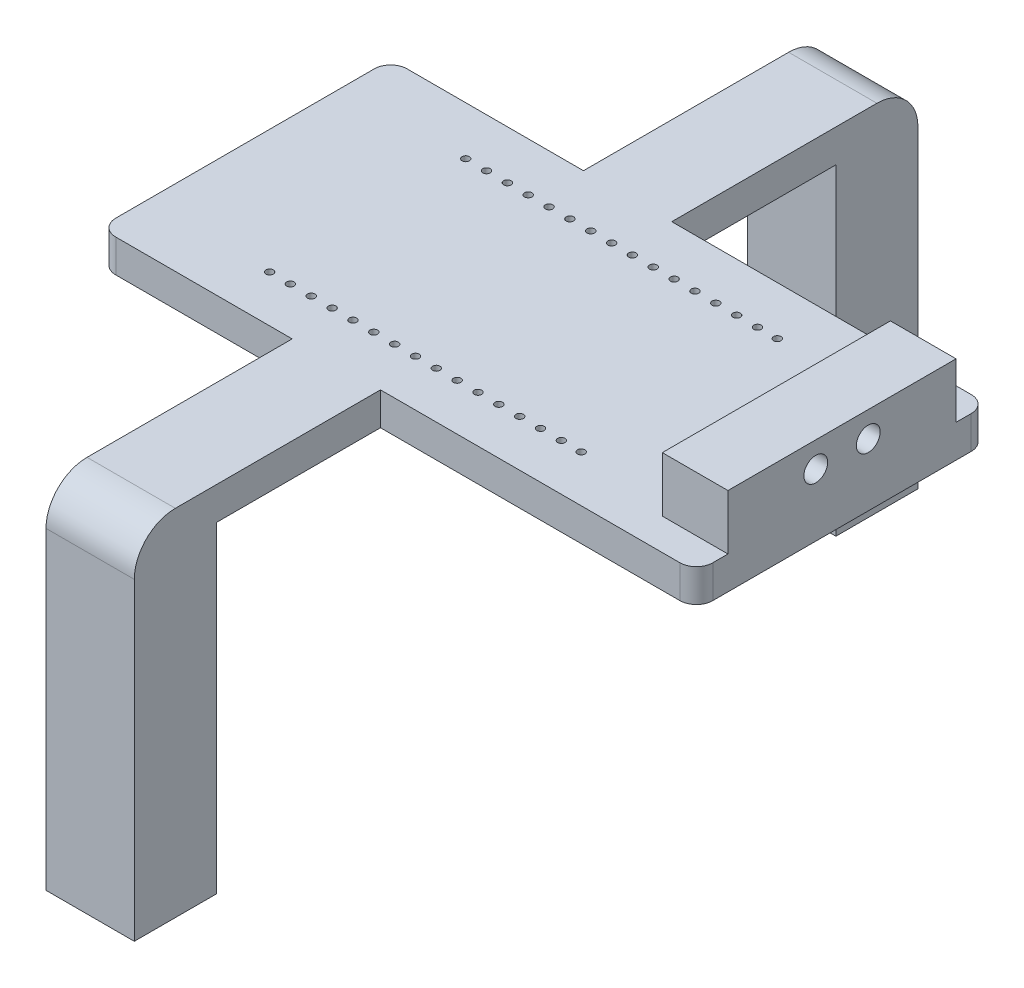
SolidWorks part; units mm, degrees
ref_plane "Front Plane" through (0, 0, 0) normal (0, 0, 1) x (1, 0, 0)
ref_plane "Top Plane" through (0, 0, 0) normal (0, 1, 0) x (1, 0, 0)
ref_plane "Right Plane" through (0, 0, 0) normal (1, 0, 0) x (0, 0, -1)
sketch "Sketch1" plane through (0, 0, 0) normal (0, 1, 0) x (1, 0, 0)
  line L7 (-5.5453, -3.1231) -> (67.2047, -3.1231)
  line L8 (-5.5453, -3.1231) -> (-5.5453, 32.3769)
  line L9 (-5.5453, 32.3769) -> (67.2047, 32.3769)
  line L10 (67.2047, -3.1231) -> (67.2047, 32.3769)
  point P0 (0, 0)
  point P18 (0, 0)
  dimension "D1" = 72.75
  dimension "D2" = 35.5
extrude "Boss-Extrude1" add sketch "Sketch1" along normal blind 2
sketch "Sketch7" plane through (0, 2, 0) normal (0, 1, 0) x (1, 0, 0)
  line L2 (17.9499, 32.3769) -> (17.9499, 62.3769)
  line L3 (17.9499, 62.3769) -> (28.7094, 62.3769)
  line L4 (28.7094, 32.3769) -> (28.7094, 62.3769)
  line L5 (23.3297, 44.5136) -> (28.7094, 62.3769) construction
  line L6 (17.9499, 62.3769) -> (23.3297, 44.5136) construction
  line L7 (17.9499, 32.3769) -> (28.7094, 32.3769)
  line L8 (67.2047, 32.3769) -> (-5.5453, 32.3769) construction
  point P0 (23.3297, 24.3769)
  point P2 (0, 0)
  dimension "D1" = 30
extrude "Boss-Extrude4" add sketch "Sketch7" against normal blind 4
sketch "Sketch8" plane through (0, 2, 0) normal (0, 1, 0) x (1, 0, 0)
  line L0 (-5.5453, 14.6269) -> (67.2047, 14.6269)
  line L1 (-5.5453, 32.3769) -> (-5.5453, -3.1231) construction
  line L2 (67.2047, -3.1231) -> (67.2047, 32.3769) construction
ref_plane "Plane2" through (0, 0, -14.6269) normal (0, 0, 1) x (1, 0, 0)
mirror "Mirror3" about plane through (0, 0, -14.6269) normal (0, 0, 1) of "Boss-Extrude4"
sketch "Sketch10" plane through (0, 2, 0) normal (0, 1, 0) x (1, 0, 0)
  line L0 (17.9499, 62.3769) -> (17.9499, 52.3769)
  line L1 (17.9499, 62.3769) -> (17.9499, 32.3769) construction
  line L2 (17.9499, 52.3769) -> (28.7094, 52.3769)
  line L3 (28.7094, 32.3769) -> (28.7094, 62.3769) construction
  line L4 (28.7094, 52.3769) -> (28.7094, 62.3769)
  line L5 (28.7094, 62.3769) -> (17.9499, 62.3769)
  dimension "D1" = 10
extrude "Boss-Extrude5" add sketch "Sketch10" against normal blind 43.2
mirror "Mirror4" about plane through (0, 0, -14.6269) normal (0, 0, 1) of "Boss-Extrude5"
fillet "Fillet2" radius 5 2 edges at (23.3297, 2, -62.3769) (23.3297, 2, 33.1231)
sketch "Sketch12" plane through (0, 0, 0) normal (0, -1, 0) x (1, 0, 0)
  line L0 (-5.5453, 3.1231) -> (67.2047, 3.1231)
  line L1 (-5.5453, 3.1231) -> (-5.5453, -32.3769)
  line L2 (67.2047, 3.1231) -> (67.2047, -32.3769)
  line L3 (-5.5453, -32.3769) -> (67.2047, -32.3769)
  line L4 (17.9499, -32.3769) -> (-5.5453, -32.3769) construction
  point P0 (0, 0)
extrude "Boss-Extrude6" add sketch "Sketch12" along normal blind 2
fillet "Fillet4" radius 2 4 edges at (67.2047, 0, 3.1231) (-5.5453, 0, 3.1231) (-5.5453, 0, -32.3769) (67.2047, 0, -32.3769)
ref_plane "Plane3" through (67.2047, 0, 0) normal (1, 0, 0) x (0, 0, -1)
sketch "Sketch16" plane through (67.2047, 0, 0) normal (1, 0, 0) x (0, 0, -1)
  line L1 (0.7269, 2) -> (28.5269, 2)
  line L3 (28.5269, 8.7) -> (28.5269, 2)
  line L5 (0.7269, 8.7) -> (28.5269, 8.7)
  line L7 (0.7269, 8.7) -> (0.7269, 2)
  line L9 (-1.1231, 2) -> (30.3769, 2) construction
  line L10 (-3.1231, -2) -> (-3.1231, 2) construction
  line L11 (32.3769, -2) -> (32.3769, 2) construction
  point P1 (14.6269, 2)
  dimension "D1" = 27.8
  dimension "D2" = 6.7
  dimension "D3" = 3.85
  dimension "D4" = 3.85
extrude "Boss-Extrude8" add sketch "Sketch16" against normal blind 8 contours L5 L3 L1 L7
sketch "Sketch19" plane through (67.2047, 0, 0) normal (1, 0, 0) x (0, 0, -1)
  line L0 (11.4269, 5.6119) -> (17.8269, 5.6119)
  line L1 (14.6269, 40.0125) -> (14.6269, -40.0125) construction
  circle A0 centre (17.8269, 5.6119) radius 1.45
  circle A1 centre (11.4269, 5.6119) radius 1.45
  point P4 (14.6269, 5.6119)
  dimension "D1" = 2.9
extrude "Cut-Extrude2" cut sketch "Sketch19" against normal blind 4
sketch "Sketch20" plane through (0, 2, 0) normal (0, 1, 0) x (1, 0, 0)
  line L0 (1.7408, 25.2114) -> (59.4908, 25.2114) construction
  line L1 (1.7408, 27.7114) -> (59.4908, 27.7114) construction
  line L2 (8.2408, 27.7114) -> (8.2408, 25.2114) construction
  line L3 (48.7558, 27.7114) -> (48.7558, 25.2114) construction
  line L4 (9.0608, 26.4614) -> (47.9358, 26.4614) construction
  line L5 (10.7808, 27.7114) -> (10.7808, 26.4614) construction
  line L6 (10.7808, 26.4614) -> (10.7808, 25.2114) construction
  line L7 (10.7808, 27.0864) -> (8.2408, 27.0864) construction
  line L8 (9.5108, 27.0864) -> (9.5108, 26.4614) construction
  line L9 (8.2408, 26.4614) -> (9.0608, 26.4614) construction
  line L10 (47.9358, 26.4614) -> (48.7558, 26.4614) construction
  line L11 (30.6158, 25.2114) -> (30.6158, 14.5114) construction
  line L12 (30.6158, 14.5114) -> (32.5949, 14.5114)
  line L13 (47.9358, 2.5614) -> (48.7558, 2.5614) construction
  line L14 (8.2408, 2.5614) -> (9.0608, 2.5614) construction
  line L15 (9.5108, 1.9364) -> (9.5108, 2.5614) construction
  line L16 (10.7808, 1.9364) -> (8.2408, 1.9364) construction
  line L17 (10.7808, 2.5614) -> (10.7808, 3.8114) construction
  line L18 (10.7808, 1.3114) -> (10.7808, 2.5614) construction
  line L19 (9.0608, 2.5614) -> (47.9358, 2.5614) construction
  line L20 (48.7558, 1.3114) -> (48.7558, 3.8114) construction
  line L21 (8.2408, 1.3114) -> (8.2408, 3.8114) construction
  circle A0 centre (9.5108, 26.4614) radius 0.45
  circle A1 centre (12.0508, 26.4614) radius 0.45
  circle A2 centre (14.5908, 26.4614) radius 0.45
  circle A3 centre (17.1308, 26.4614) radius 0.45
  circle A4 centre (19.6708, 26.4614) radius 0.45
  circle A5 centre (22.2108, 26.4614) radius 0.45
  circle A6 centre (24.7508, 26.4614) radius 0.45
  circle A7 centre (27.2908, 26.4614) radius 0.45
  circle A8 centre (29.8308, 26.4614) radius 0.45
  circle A9 centre (32.3708, 26.4614) radius 0.45
  circle A10 centre (34.9108, 26.4614) radius 0.45
  circle A11 centre (37.4508, 26.4614) radius 0.45
  circle A12 centre (39.9908, 26.4614) radius 0.45
  circle A13 centre (42.5308, 26.4614) radius 0.45
  circle A14 centre (45.0708, 26.4614) radius 0.45
  circle A15 centre (47.4858, 26.4614) radius 0.45
  circle A16 centre (47.4858, 2.5614) radius 0.45
  circle A17 centre (45.0708, 2.5614) radius 0.45
  circle A18 centre (42.5308, 2.5614) radius 0.45
  circle A19 centre (39.9908, 2.5614) radius 0.45
  circle A20 centre (37.4508, 2.5614) radius 0.45
  circle A21 centre (34.9108, 2.5614) radius 0.45
  circle A22 centre (32.3708, 2.5614) radius 0.45
  circle A23 centre (29.8308, 2.5614) radius 0.45
  circle A24 centre (27.2908, 2.5614) radius 0.45
  circle A25 centre (24.7508, 2.5614) radius 0.45
  circle A26 centre (22.2108, 2.5614) radius 0.45
  circle A27 centre (19.6708, 2.5614) radius 0.45
  circle A28 centre (17.1308, 2.5614) radius 0.45
  circle A29 centre (14.5908, 2.5614) radius 0.45
  circle A30 centre (12.0508, 2.5614) radius 0.45
  circle A31 centre (9.5108, 2.5614) radius 0.45
  dimension "D2" = 0.9
  dimension "D3" = 0.9
  dimension "D4" = 0.9
  dimension "D5" = 0.9
  dimension "D6" = 0.9
  dimension "D7" = 0.9
  dimension "D8" = 0.9
  dimension "D9" = 0.9
  dimension "D10" = 0.9
  dimension "D11" = 0.9
  dimension "D12" = 0.9
  dimension "D13" = 0.9
  dimension "D14" = 0.9
  dimension "D15" = 0.9
  dimension "D16" = 0.9
  dimension "D1" = 10.7
extrude "Cut-Extrude3" cut sketch "Sketch20" against normal through all contours A0 | A1 | A3 | A15 | A14 | A11 | A8 | A2 | A13 | A12 | A10 | A9 | A7 | A6 | A5 | A4 | A31 | A30 | A29 | A28 | A27 | A26 | A25 | A23 | A22 | A21 | A24 | A19 | A20 | A18 | A16 | A17
sketch "Sketch21" plane through (0, -41.2, 0) normal (0, -1, 0) x (1, 0, 0)
  line L0 (17.9499, 33.1231) -> (28.7094, 23.1231) construction
  circle A0 centre (23.3297, 28.1231) radius 3.1
extrude "Cut-Extrude4" cut sketch "Sketch21" against normal blind 5
mirror "Mirror5" about plane through (0, 0, -14.6269) normal (0, 0, 1) of "Cut-Extrude4"
